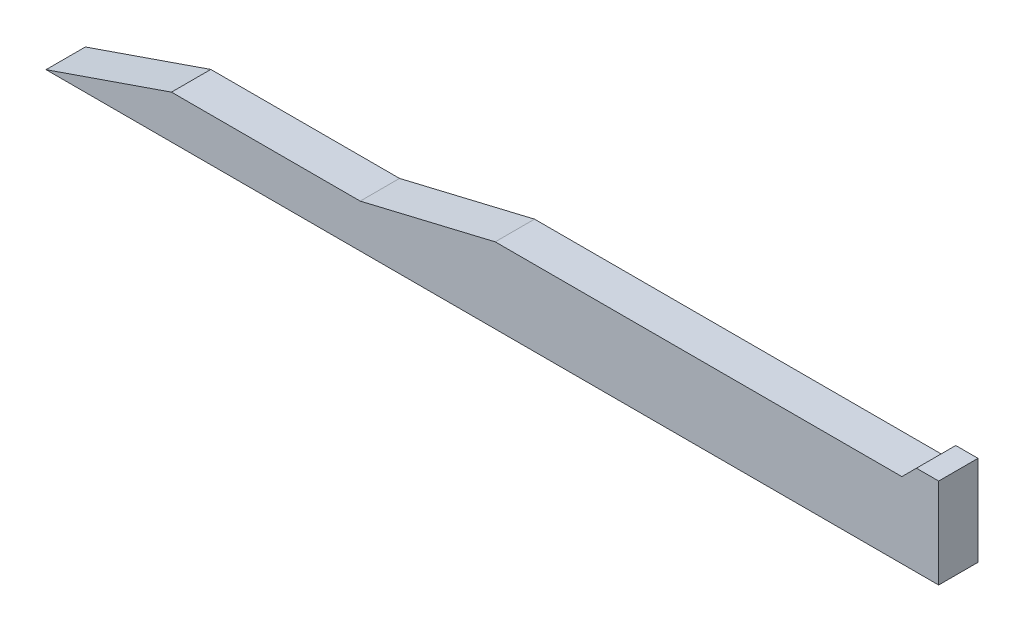
SolidWorks part; units mm, degrees
ref_plane "Front Plane" through (0, 0, 0) normal (0, 0, 1) x (1, 0, 0)
ref_plane "Top Plane" through (0, 0, 0) normal (0, 1, 0) x (1, 0, 0)
ref_plane "Right Plane" through (0, 0, 0) normal (1, 0, 0) x (0, 0, -1)
sketch "Sketch1" plane through (0, 0, 0) normal (0, 0, 1) x (1, 0, 0)
  line L0 (0, 0) -> (15.9539, 5.503)
  line L1 (15.9539, 5.503) -> (39.9503, 5.503)
  line L2 (39.9503, 5.503) -> (57.1185, 9.6)
  line L3 (57.1185, 9.6) -> (108.818, 9.6)
  line L4 (108.818, 9.6) -> (110.6714, 11.4533)
  line L5 (110.6714, 11.4533) -> (113.5002, 11.4533)
  line L6 (113.5002, 11.4533) -> (113.5002, 0)
  line L7 (113.5002, 0) -> (0, 0)
extrude "Boss-Extrude1" add sketch "Sketch1" along normal blind 5
